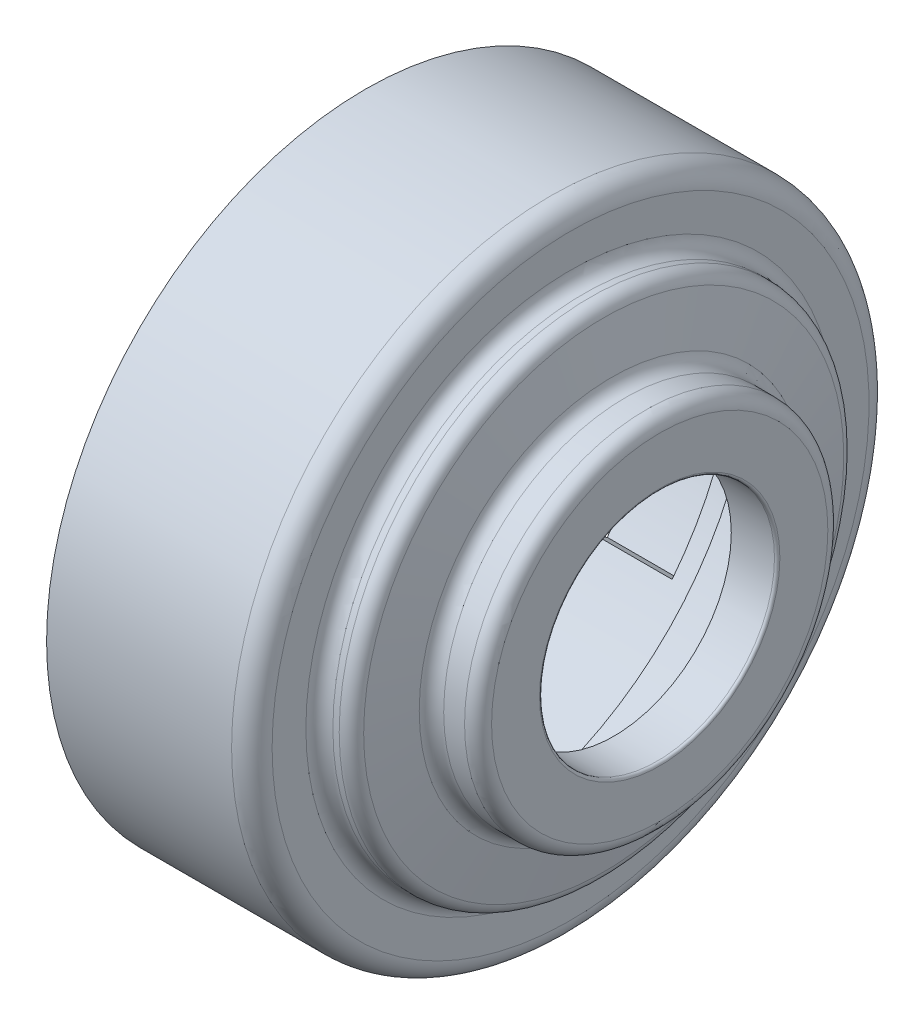
SolidWorks part; units mm, degrees
ref_plane "前视基准面" through (0, 0, 0) normal (0, 0, 1) x (1, 0, 0)
ref_plane "上视基准面" through (0, 0, 0) normal (0, 1, 0) x (1, 0, 0)
ref_plane "右视基准面" through (0, 0, 0) normal (1, 0, 0) x (0, 0, -1)
sketch "草图2" plane through (0, 0, 0) normal (0, 0, 1) x (1, 0, 0)
  line L0 (-36.9366, 0) -> (44.5849, 0) construction
  line L1 (0, 36.0368) -> (0, -37.1166) construction
  line L2 (-14, 22) -> (-6.9, 22)
  line L3 (-6.9, 22) -> (-6.9, 21.6)
  line L4 (-6.9, 21.6) -> (0, 21.6)
  line L5 (0, 21.6) -> (0, 17.4)
  line L6 (0, 17.4) -> (2.5, 17.4)
  line L8 (3.4081, 12.25) -> (6.6, 12.25)
  line L9 (6.6, 12.25) -> (6.6, 9.4)
  line L10 (6.6, 9.4) -> (4.4, 9.4)
  line L11 (4.4, 9.4) -> (4.4, 8.7)
  line L12 (4.4, 8.7) -> (7.8, 8.7)
  line L13 (-14, 22) -> (-14, 23.6)
  line L14 (-14, 23.6) -> (1.2, 23.6)
  line L15 (1.2, 23.6) -> (1.2, 18.6)
  line L16 (1.2, 18.6) -> (3.5069, 18.6)
  line L18 (4.415, 13.45) -> (7.8, 13.45)
  line L19 (7.8, 13.45) -> (7.8, 8.7)
  line L20 (2.5, 17.4) -> (3.4081, 12.25)
  line L21 (3.5069, 18.6) -> (4.415, 13.45)
  dimension "D1" = 44
  dimension "D2" = 0.4
  dimension "D3" = 7.1
  dimension "D4" = 14
  dimension "D5" = 34.8
  dimension "D6" = 2.5
  dimension "D7" = 18.8
  dimension "D8" = 0.7
  dimension "D9" = 4.4
  dimension "D10" = 2.2
  dimension "D11" = 24.5
  dimension "D12" = 47.2
  dimension "D13" = 2
  dimension "D14" = 1.2
  dimension "D15" = 10
  dimension "D16" = 1.2
  dimension "D17" = 1.2
  dimension "D18" = 1.2
  dimension "D19" = 1.2
  dimension "D20" = 1.6
revolve "旋转1" add sketch "草图2" angle 360 about L0
fillet "圆角1" radius 0.2 5 edges at (0, 0, 17.4) (0, 0, 21.6) (7.8, 0, 8.7) (6.6, 0, 12.25) (2.5, 0, 17.4)
fillet "圆角2" radius 1 4 edges at (1.2, 0, 18.6) (7.8, 0, 13.45) (3.5069, 0, 18.6) (4.415, 0, 13.45)
fillet "圆角3" radius 1.5 2 edges at (1.2, 0, 23.6) (3.4081, 0, 12.25)
sketch "草图3" plane through (-14, 0, 0) normal (-1, 0, 0) x (0, 0, 1)
  line L0 (0, 27.1942) -> (0, -25.474) construction
  line L1 (-27.7353, 0) -> (28.2343, 0) construction
  line L2 (-0.5, 22.6) -> (0.5, 22.6)
  line L3 (-0.5, 22.6) -> (-0.5, 21.9943)
  line L4 (0.5, 22.6) -> (0.5, 21.9943)
  circle A0 centre (0, 0) radius 22 construction
  arc A1 (0.5, 21.9943) -> (-0.5, 21.9943) centre (0, 0) ccw
  point P7 (0, 22)
  point P14 (0, 22.6)
  dimension "D1" = 1
  dimension "D2" = 0.6
extrude "切除-拉伸1" cut sketch "草图3" against normal blind 1
sketch "草图4" plane through (-14, 0, 0) normal (-1, 0, 0) x (0, 0, 1)
  line L0 (0, 29.159) -> (0, -31.1439) construction
  line L1 (-35.4917, 0) -> (32.6562, 0) construction
  line L2 (-3.25, 22.5672) -> (-3.25, 21.7586)
  line L3 (3.25, 22.5672) -> (3.25, 21.7586)
  circle A0 centre (0, 0) radius 22 construction
  arc A1 (3.25, 21.7586) -> (-3.25, 21.7586) centre (0, 0) ccw
  arc A2 (3.25, 22.5672) -> (-3.25, 22.5672) centre (0, 0) ccw
  dimension "D2" = 22.8
  dimension "D1" = 6.5
  dimension "D3" = 3.25
extrude "切除-拉伸2" cut sketch "草图4" against normal blind 5.5
sketch "草图5" plane through (0, 0, 0) normal (0, 0, 1) x (1, 0, 0)
  line L0 (16.6242, 0) -> (-23.7431, 0) construction
  line L1 (0, 27.01) -> (0, -27.8633) construction
  line L2 (-8.5, 22.8) -> (-8.5, 21.3419)
  line L3 (-8.5, 21.3419) -> (-10.7, 21.3419)
  line L4 (-10.7, 21.3419) -> (-10.7, 22.8)
  line L5 (-10.7, 22.8) -> (-8.5, 22.8)
  line L7 (-14, -0.1207) -> (-14, 29.419) construction
  line L8 (-14, 21.7586) -> (-14, -22) construction
  dimension "D1" = 3.3
  dimension "D2" = 2.2
  dimension "D3" = 45.6
revolve "切除-旋转1" cut sketch "草图5" angle 24 about L0
ref_plane "基准面1" through (0, 18, 0) normal (0, 1, 0) x (1, 0, 0)
sketch "草图6" plane through (0, 18, 0) normal (0, 1, 0) x (1, 0, 0)
  line L0 (16.0352, 0) -> (-25.287, 0) construction
  line L1 (-10.7, -8.9482) -> (-10.7, -3.25) construction
  line L2 (-10.7, -8.9482) -> (-10.7, -3.25)
  line L3 (-10.7, -3.25) -> (-10.7995, -8.9482)
  line L5 (-10.7, -8.9482) -> (-10.7995, -8.9482)
  dimension "D1" = 1
extrude "切除-拉伸3" cut sketch "草图6" along normal up to surface (2.9707 mm away)
pattern_circular "阵列(圆周)1" count 3 over 360 about axis through (0, 0, 0) along (1, 0, 0) of "切除-拉伸2", "切除-旋转1"
sketch "草图9" plane through (-10.7, 0, 0) normal (1, 0, 0) x (0, 0, -1)
  line L0 (-9.2736, 20.8288) -> (-8.9482, 20.098) construction
  line L1 (-8.9482, 20.9707) -> (-8.9482, 20.098) construction
  line L2 (-9.2736, 20.8288) -> (-8.9482, 20.098)
  line L3 (-8.9482, 20.9707) -> (-8.9482, 20.098)
  arc A0 (-8.9482, 20.9707) -> (-9.2736, 20.8288) centre (0, 0) ccw construction
  arc A1 (-8.9482, 20.9707) -> (-9.2736, 20.8288) centre (0, 0) ccw
extrude "切除-拉伸5" cut sketch "草图9" against normal up to surface (0.0995 mm away)
pattern_circular "阵列(圆周)3" count 3 over 360 about axis through (0, 0, 0) along (1, 0, 0) of "切除-拉伸3"
sketch "草图10" plane through (-10.7, 0, 0) normal (1, 0, 0) x (0, 0, -1)
  line L2 (22.6751, -2.3832) -> (21.8795, -2.2996)
  line L3 (21.8795, -2.2996) -> (22.6352, -2.736)
  line L4 (22.6751, -2.3832) -> (21.8795, -2.2996)
  line L5 (21.8795, -2.2996) -> (22.6352, -2.736)
  arc A1 (22.6352, -2.736) -> (22.6751, -2.3832) centre (0, 0) ccw
  arc A2 (22.6352, -2.736) -> (22.6751, -2.3832) centre (0, 0) ccw
  dimension "D1" = 0
extrude "切除-拉伸6" cut sketch "草图10" against normal up to surface (0.0995 mm away)
sketch "草图11" plane through (-10.7, 0, 0) normal (1, 0, 0) x (0, 0, -1)
  line L2 (-13.4015, -18.4456) -> (-12.9313, -17.7984)
  line L3 (-12.9313, -17.7984) -> (-13.687, -18.2347)
  line L4 (-13.4015, -18.4456) -> (-12.9313, -17.7984)
  line L5 (-12.9313, -17.7984) -> (-13.687, -18.2347)
  arc A1 (-13.687, -18.2347) -> (-13.4015, -18.4456) centre (0, 0) ccw
  arc A2 (-13.687, -18.2347) -> (-13.4015, -18.4456) centre (0, 0) ccw
  dimension "D1" = 0
extrude "切除-拉伸7" cut sketch "草图11" against normal up to surface (0.0995 mm away)
